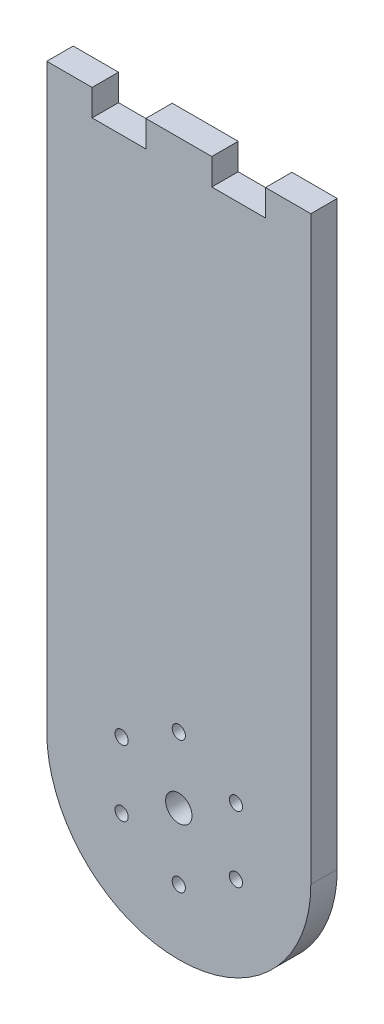
SolidWorks part; units mm, degrees
ref_plane "Alzado" through (0, 0, 0) normal (0, 0, 1) x (1, 0, 0)
ref_plane "Planta" through (0, 0, 0) normal (0, 1, 0) x (1, 0, 0)
ref_plane "Vista lateral" through (0, 0, 0) normal (1, 0, 0) x (0, 0, -1)
sketch "Sketch2" plane through (0, 0, 0) normal (0, 0, 1) x (1, 0, 0)
  line L0 (-9.85, 40.45) -> (-9.85, 37.45)
  line L1 (-15, 40.45) -> (-9.85, 40.45)
  line L2 (-15, 40.45) -> (-15, -25.55)
  line L3 (-0.1, -40.45) -> (0.1, -40.45)
  line L4 (15, 40.45) -> (15, -25.55)
  line L5 (-15, 40.45) -> (15, -40.45) construction
  line L6 (-15, -40.45) -> (15, 40.45) construction
  line L7 (-9.85, 37.45) -> (-3.75, 37.45)
  line L8 (-3.75, 37.45) -> (-3.75, 40.45)
  line L9 (3.75, 40.45) -> (3.75, 37.45)
  line L10 (3.75, 37.45) -> (9.85, 37.45)
  line L11 (9.85, 37.45) -> (9.85, 40.45)
  line L12 (-15, 7.45) -> (15, 7.45) construction
  line L13 (-3.75, 40.45) -> (3.75, 40.45)
  line L14 (9.85, 40.45) -> (15, 40.45)
  line L15 (0, 40.45) -> (0, 0) construction
  line L16 (0, 0) -> (-1.6849, -4.5435) construction
  line L17 (0, -25.55) -> (0, 0) construction
  line L18 (-15, -25.55) -> (0, -25.55) construction
  line L19 (-6.4952, -21.8) -> (6.4952, -29.3) construction
  line L20 (6.4952, -21.8) -> (-6.4952, -29.3) construction
  line L21 (0, -25.55) -> (0, -33.05) construction
  circle A0 centre (0, -25.55) radius 7.5 construction
  arc A1 (0.1, -40.45) -> (15, -25.55) centre (0.1, -25.55) ccw
  arc A2 (-15, -25.55) -> (-0.1, -40.45) centre (-0.1, -25.55) ccw
  circle A3 centre (0, -18.05) radius 0.75
  circle A4 centre (6.4952, -21.8) radius 0.75
  circle A5 centre (6.4952, -29.3) radius 0.75
  circle A6 centre (0, -33.05) radius 0.75
  circle A7 centre (-6.4952, -29.3) radius 0.75
  circle A8 centre (-6.4952, -21.8) radius 0.75
  circle A9 centre (0, -25.55) radius 1.5
  point P0 (0, 0)
  point P20 (0, -25.55)
  point P43 (0, -25.55)
  dimension "D6" = 14.9
  dimension "D9" = 15
  dimension "D12" = 1.5
  dimension "D13" = 3
  dimension "D1" = 3
  dimension "D2" = 30
  dimension "D3" = 5.15
  dimension "D4" = 5.15
  dimension "D5" = 7.5
  dimension "D7" = 60
  dimension "D8" = 63
  dimension "D10" = 60
  dimension "D11" = 60
extrude "Boss-Extrude1" add sketch "Sketch2" along normal blind 3
